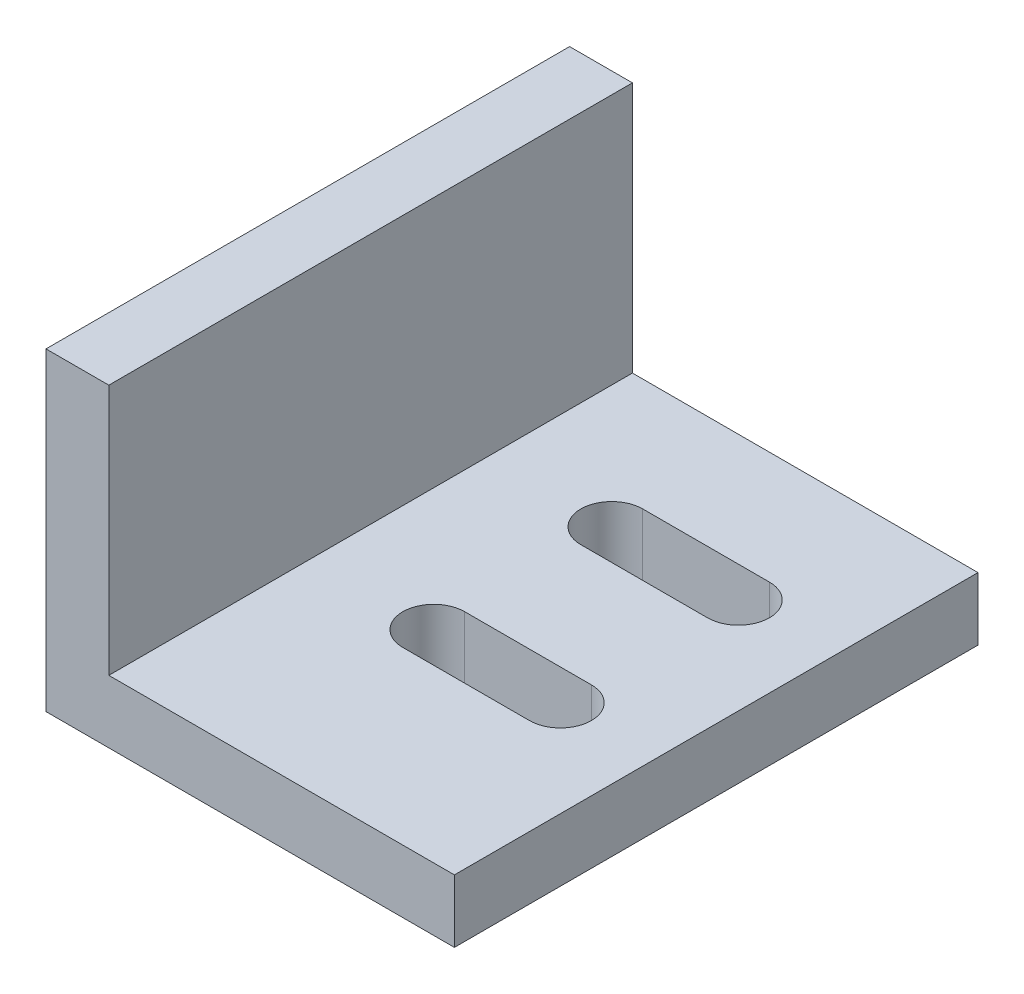
SolidWorks part; units mm, degrees
ref_plane "Front Plane" through (0, 0, 0) normal (0, 0, 1) x (1, 0, 0)
ref_plane "Top Plane" through (0, 0, 0) normal (0, 1, 0) x (1, 0, 0)
ref_plane "Right Plane" through (0, 0, 0) normal (1, 0, 0) x (0, 0, -1)
sketch "Sketch1" plane through (0, 0, 0) normal (0, 0, 1) x (1, 0, 0)
  line L0 (0, 0) -> (-39, 0)
  line L1 (-39, 0) -> (-39, 30)
  line L2 (-39, 30) -> (-33, 30)
  line L3 (-33, 30) -> (-33, 6)
  line L4 (-33, 6) -> (0, 6)
  line L5 (0, 6) -> (0, 0)
  dimension "D1" = 6
  dimension "D2" = 6
  dimension "D3" = 33
  dimension "D4" = 30
extrude "Boss-Extrude1" add sketch "Sketch1" along normal blind 50
sketch "Sketch2" plane through (0, 0, 0) normal (0, -1, 0) x (1, 0, 0)
  line L10 (-15.2234, 8.7) -> (13.9766, 8.7)
  line L11 (13.9766, 8.7) -> (13.9766, 50)
  line L12 (13.9766, 50) -> (-15.2234, 50)
  line L13 (-15.2234, 50) -> (-15.2234, 33.656)
  line L14 (-15.2234, 33.656) -> (-9.1734, 33.656)
  line L15 (-9.1734, 27.744) -> (-15.2234, 27.744)
  line L16 (-15.2234, 27.744) -> (-15.2234, 16.656)
  line L17 (-15.2234, 16.656) -> (-9.1734, 16.656)
  line L18 (-9.1734, 10.744) -> (-15.2234, 10.744)
  line L19 (-15.2234, 10.744) -> (-15.2234, 8.7)
  line L24 (-21.2734, 33.656) -> (-9.1734, 33.656)
  line L25 (-9.1734, 27.744) -> (-21.2734, 27.744)
  line L27 (-21.2734, 16.656) -> (-9.1734, 16.656)
  line L28 (-9.1734, 10.744) -> (-21.2734, 10.744)
  arc A0 (-21.2734, 27.744) -> (-21.2734, 33.656) centre (-21.2734, 30.7) cw
  arc A1 (-21.2734, 10.744) -> (-21.2734, 16.656) centre (-21.2734, 13.7) cw
  arc A2 (-9.1734, 27.744) -> (-9.1734, 33.656) centre (-9.1734, 30.7) ccw
  arc A3 (-9.1734, 10.744) -> (-9.1734, 16.656) centre (-9.1734, 13.7) ccw
  arc A4 (-9.1734, 27.744) -> (-9.1734, 33.656) centre (-9.1734, 30.7) ccw
  arc A5 (-9.1734, 10.744) -> (-9.1734, 16.656) centre (-9.1734, 13.7) ccw
  dimension "D1" = 0
extrude "Cut-Extrude1" cut sketch "Sketch2" against normal blind 14
